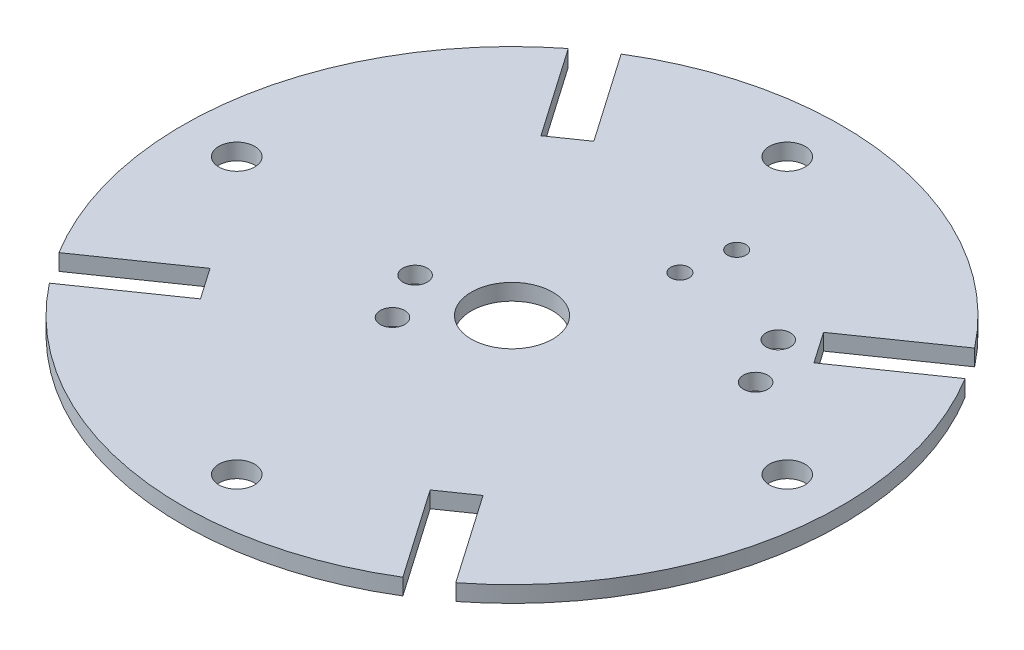
SolidWorks part; units mm, degrees
material "S-Glass Fiber"
ref_plane "Front Plane" through (0, 0, 0) normal (0, 0, 1) x (1, 0, 0)
ref_plane "Top Plane" through (0, 0, 0) normal (0, 1, 0) x (1, 0, 0)
ref_plane "Right Plane" through (0, 0, 0) normal (1, 0, 0) x (0, 0, -1)
sketch "Sketch1" plane through (0, 0, 0) normal (0, 1, 0) x (1, 0, 0)
  circle A0 centre (0, 0) radius 60.7
  dimension "Diameter" = 121.4
extrude "Boss-Extrude1" add sketch "Sketch1" along normal mid plane 3
hole_wizard "M6 Clearance Hole1" positions "Sketch8" profile "Sketch9" hole size "M6" standard "ANSI Metric" end condition up to next
sketch "Sketch8" plane through (0, 1.5, 0) normal (0, 1, 0) x (1, 0, 0)
  line L0 (0, 0) -> (50.7, 0) construction
  point P0 (50.7, 0)
  dimension "ThreadedHoleDistance" = 50.7
sketch "Sketch9" plane through (50.7, 1.5, 0) normal (1, 0, 0) x (0, 0, 1)
  line L0 (0, 0) -> (0, 3)
  line L1 (0, 3) -> (3.3, 3)
  line L2 (3.3, 3) -> (3.3, 0)
  line L5 (3.3, 0) -> (0, 0)
  line L11 (0, -6.35) -> (0, 107.95) construction
  dimension "Thru Hole Dia." = 6.6
  dimension "Thru Hole Depth" = 3
pattern_circular "CirPattern2" count 4 over 360 about axis through (0, 0, 0) along (0, 1, 0) of "M6 Clearance Hole1"
sketch "Sketch5" plane through (0, 1.5, 0) normal (0, 1, 0) x (1, 0, 0)
  line L0 (0, 0) -> (60.7, 0) construction
  line L2 (0, 0) -> (35.8503, 35.8503) construction
  circle A0 centre (0, 0) radius 60.7 construction
  dimension "D1" = 45
  dimension " NoseShellHoleRadius" = 50.7
hole_wizard "M4 Clearance Hole1" positions "Sketch6" profile "Sketch7" hole size "M4" standard "ANSI Metric"
sketch "Sketch6" plane through (0, 1.5, 0) normal (0, 1, 0) x (1, 0, 0)
  point P0 (39.1737, 39.1737)
sketch "Sketch7" plane through (39.1737, 1.5, -39.1737) normal (1, 0, 0) x (0, 0, 1)
  line L0 (0, 0) -> (0, 3)
  line L1 (0, 3) -> (2.15, 3)
  line L2 (2.15, 3) -> (2.15, 0)
  line L5 (2.15, 0) -> (0, 0)
  line L11 (0, -6.35) -> (0, 107.95) construction
  dimension "Thru Hole Dia." = 4.3
  dimension "Thru Hole Depth" = 3
pattern_circular "CirPattern1" [suppressed] count 4 over 360
sketch "Sketch10" plane through (0, 1.5, 0) normal (0, 1, 0) x (1, 0, 0)
  circle A0 centre (0, 0) radius 7.5
  dimension "D1" = 15
extrude "servo hub hole" cut sketch "Sketch10" against normal through all
sketch "Sketch11" plane through (0, -1.5, 0) normal (0, -1, 0) x (1, 0, 0)
  line L0 (-10.7064, 11.3108) -> (33.0615, -11.8109) construction
  line L1 (33.0615, -11.8109) -> (28.3905, -20.6529) construction
  line L2 (28.3905, -20.6529) -> (-15.3775, 2.4688) construction
  line L3 (-15.3775, 2.4688) -> (-10.7064, 11.3108) construction
  line L4 (2.3355, 4.421) -> (-2.3355, -4.421) construction
  line L5 (50.7, 23.5936) -> (50.7, -21.734) construction
  circle A0 centre (-15.3775, 2.4688) radius 2.25
  circle A2 centre (-10.7064, 11.3108) radius 2.25
  circle A3 centre (28.3905, -20.6529) radius 2.25
  circle A4 centre (33.0615, -11.8109) radius 2.25
  point P2 (50.7, 0)
  point P12 (50.7, 0)
  dimension "D1" = 10
  dimension "D2" = 49.5
  dimension "D4" = 4.5
  dimension "D3" = 14.75
  dimension "D5" = 17.6385
extrude "servo screw holes" cut sketch "Sketch11" against normal through all
sketch "Sketch12" plane through (0, 1.5, 0) normal (0, 1, 0) x (1, 0, 0)
  circle A0 centre (0, 0) radius 60.7 construction
  circle A1 centre (0, 0) radius 60.7
sketch "Sketch13" plane through (0, 1.5, 0) normal (0, 1, 0) x (1, 0, 0)
  line L0 (31.6774, -51.7787) -> (20.2737, -35.3484)
  line L1 (20.2737, -35.3484) -> (26.0243, -31.3571)
  line L2 (26.0243, -31.3571) -> (37.428, -47.7874)
  line L3 (23.149, -33.3527) -> (34.6103, -49.866) construction
  line L4 (23.149, -33.3527) -> (0, 0) construction
  line L5 (0, 0) -> (0, -50.7) construction
  line L6 (-7.3072, -48.0722) -> (-7.2822, -48.1318)
  line L7 (-7.3072, -48.0722) -> (-7.2822, -48.1318) construction
  line L8 (5.9654, -54.6476) -> (4.6633, -61.2016)
  line L9 (5.9654, -54.6476) -> (4.6633, -61.2016) construction
  line L10 (-13.8383, -61.9557) -> (-10.6131, -45.7223)
  line L11 (-13.8383, -61.9557) -> (-10.6131, -45.7223) construction
  line L12 (-10.6131, -45.7223) -> (-9.717, -41.2115)
  line L13 (-10.6131, -45.7223) -> (-9.717, -41.2115) construction
  line L14 (-9.717, -41.2115) -> (-8.0847, -32.9958)
  line L15 (-9.717, -41.2115) -> (-8.0847, -32.9958) construction
  line L16 (-8.0847, -32.9958) -> (-7.2796, -28.9433)
  line L17 (-8.0847, -32.9958) -> (-7.2796, -28.9433) construction
  line L18 (-7.2796, -28.9433) -> (-2.2975, -3.8666)
  line L19 (-7.2796, -28.9433) -> (-2.2975, -3.8666) construction
  line L20 (-2.2975, -3.8666) -> (0.645, -4.4512)
  line L21 (-2.2975, -3.8666) -> (0.645, -4.4512) construction
  line L22 (0.645, -4.4512) -> (-4.3371, -29.5279)
  line L23 (0.645, -4.4512) -> (-4.3371, -29.5279) construction
  line L24 (-4.3371, -29.5279) -> (-5.1422, -33.5804)
  line L25 (-4.3371, -29.5279) -> (-5.1422, -33.5804) construction
  line L26 (-5.1422, -33.5804) -> (-6.7745, -41.7961)
  line L27 (-5.1422, -33.5804) -> (-6.7745, -41.7961) construction
  line L28 (-6.7745, -41.7961) -> (-7.6706, -46.3069)
  line L29 (-6.7745, -41.7961) -> (-7.6706, -46.3069) construction
  circle A0 centre (0, 0) radius 60.7 construction
  circle A1 centre (0, 0) radius 60.7
  arc A2 (31.6774, -51.7787) -> (37.428, -47.7874) centre (0, 0) ccw
  arc A3 (-7.2822, -48.1318) -> (0.9663, -48.6742) centre (0.0376, 0.1893) ccw
  arc A4 (-7.2822, -48.1318) -> (0.9663, -48.6742) centre (0.0376, 0.1893) ccw construction
  arc A5 (5.9654, -54.6476) -> (0.9663, -48.6742) centre (1.0613, -53.6733) ccw
  arc A6 (5.9654, -54.6476) -> (0.9663, -48.6742) centre (1.0613, -53.6733) ccw construction
  arc A7 (-0.2638, -65.2272) -> (4.6633, -61.2016) centre (-0.2408, -60.2272) ccw
  arc A8 (-0.2638, -65.2272) -> (4.6633, -61.2016) centre (-0.2408, -60.2272) ccw construction
  arc A9 (-10.5087, -64.3722) -> (-0.2638, -65.2272) centre (0.0376, 0.1893) ccw
  arc A10 (-10.5087, -64.3722) -> (-0.2638, -65.2272) centre (0.0376, 0.1893) ccw construction
  spline S0 degree 3 poles (-551.2401, -1989.1462) (50.0288, -68.781) (14.129, -77.903) (-12.3758, -63.3729) (-13.1243, -62.9075) (-13.5648, -62.5349) (-13.7339, -62.3268) (-13.8027, -62.2127) (-15.0189, -58.3926) (38.8624, -44.8611) (-1938.6166, -603.9894) knots -20.640029 -20.640029 -20.640029 -20.640029 0.25 0.5 0.75 0.875 0.90625 0.9375 0.96875 3.776366 3.776366 3.776366 3.776366 only from (-10.5087, -64.3722) to (-13.8383, -61.9557)
  spline S1 degree 3 poles (-10.5087, -64.3722) (-10.8215, -64.2088) (-11.4465, -63.8823) (-12.3758, -63.3729) (-13.1243, -62.9075) (-13.5648, -62.5349) (-13.7339, -62.3268) (-13.8027, -62.2127) (-13.8424, -62.0879) (-13.8422, -62) (-13.8383, -61.9557) knots 0 0 0 0 0.25 0.5 0.75 0.875 0.90625 0.9375 0.96875 1 1 1 1 construction
  spline S2 degree 3 poles (-2007.5395, -26.5371) (24.5172, -34.5901) (-7.4927, -40.4891) (-7.7013, -46.6474) (-7.6977, -46.7608) (-7.6875, -46.8738) (-7.6712, -46.9863) (-7.6495, -47.098) (-7.5964, -47.3201) (-3.9019, -58.2167) (28.3656, -59.8352) (-1894.3117, -710.4228) knots -9.916956 -9.916956 -9.916956 -9.916956 0.125 0.1875 0.25 0.3125 0.375 0.4375 0.5 0.75 19.205225 19.205225 19.205225 19.205225 only from (-7.6706, -46.3069) to (-7.3072, -48.0722)
  spline S3 degree 3 poles (-7.6706, -46.3069) (-7.6813, -46.3825) (-7.6961, -46.496) (-7.7013, -46.6474) (-7.6977, -46.7608) (-7.6875, -46.8738) (-7.6712, -46.9863) (-7.6495, -47.098) (-7.5964, -47.3201) (-7.4857, -47.6466) (-7.3668, -47.9303) (-7.3072, -48.0722) knots 0 0 0 0 0.125 0.1875 0.25 0.3125 0.375 0.4375 0.5 0.75 1 1 1 1 construction
  dimension "D2" = 7
  dimension "D3" = 20
  dimension "D4" = 46
  dimension "D1" = 0
extrude "leg mechanism cutouts" cut sketch "Sketch13" against normal through all
pattern_circular "CirPattern3" count 4 over 360 about axis through (0, 0, 0) along (0, 1, 0) of "leg mechanism cutouts"
sketch "Sketch14" [suppressed] plane through (0, 1.5, 0) normal (0, 1, 0) x (1, 0, 0)
  line L0 (-23.3345, 23.3345) -> (0, 0) construction
  line L1 (0, 0) -> (-31.2562, 0) construction
  circle A0 centre (-23.3345, 23.3345) radius 3
  dimension "D1" = 6
  dimension "D2" = 45
  dimension "D3" = 33
extrude "eyebolt hole" [suppressed] cut sketch "Sketch14" against normal through all
sketch "Sketch15" [suppressed] plane through (0, 1.5, 0) normal (0, 1, 0) x (1, 0, 0)
  line L0 (0, 0) -> (-23.3345, 23.3345) construction
  line L1 (5.1764, 19.3185) -> (0, 0) construction
  line L2 (0, 0) -> (-19.3185, -5.1764) construction
  line L3 (0, 0) -> (14.1421, -14.1421) construction
  circle A0 centre (-23.3345, 23.3345) radius 3 construction
  circle A1 centre (5.1764, 19.3185) radius 12.7
  circle A2 centre (-19.3185, -5.1764) radius 12.7
  circle A3 centre (14.1421, -14.1421) radius 12.7
  dimension "D1" = 25.4
  dimension "D3" = 120
  dimension "D2" = 20
  dimension "D4" = 120
extrude "Cut-Extrude1" [suppressed] cut sketch "Sketch15" against normal through all
hole_wizard "M3 Clearance Hole1" positions "Sketch17" profile "Sketch18" hole size "M3" standard "ANSI Metric" end condition through all
sketch "Sketch17" plane through (0, 1.5, 0) normal (0, 1, 0) x (1, 0, 0)
  line L0 (14.3281, 79.3398) -> (0, 0) construction
  line L3 (10.2042, 31.1829) -> (8.6047, 22.3262) construction
  line L4 (8.6047, 22.3262) -> (4.1764, 23.1259) construction
  point P9 (10.2042, 31.1829)
  point P10 (8.6047, 22.3262)
  dimension "D1" = 9
  dimension "D2" = 4.5
  dimension "D3" = 23.5
sketch "Sketch18" plane through (8.6047, 1.5, -22.3262) normal (1, 0, 0) x (0, 0, 1)
  line L0 (0, 0) -> (0, 3)
  line L1 (0, 3) -> (1.7, 3)
  line L2 (1.7, 3) -> (1.7, 0)
  line L5 (1.7, 0) -> (0, 0)
  line L11 (0, -6.35) -> (0, 107.95) construction
  dimension "Thru Hole Dia." = 3.4
  dimension "Thru Hole Depth" = 3
